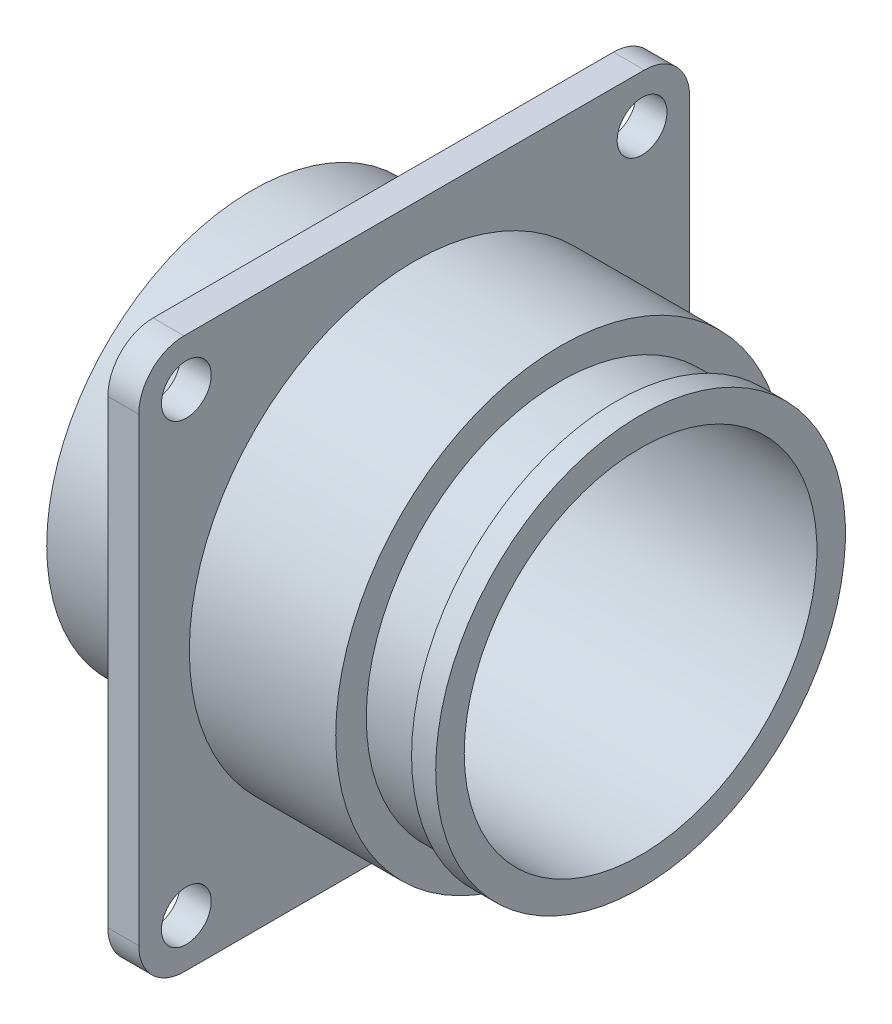
SolidWorks part; units mm, degrees
ref_plane "Alzado" through (0, 0, 0) normal (0, 0, 1) x (1, 0, 0)
ref_plane "Planta" through (0, 0, 0) normal (0, 1, 0) x (1, 0, 0)
ref_plane "Vista lateral" through (0, 0, 0) normal (1, 0, 0) x (0, 0, -1)
sketch "Croquis1" plane through (0, 0, 0) normal (1, 0, 0) x (0, 0, -1)
  line L1 (-15.25, -18.25) -> (15.25, -18.25)
  line L2 (-18.25, -15.25) -> (-18.25, 15.25)
  line L3 (-15.25, 18.25) -> (15.25, 18.25)
  line L4 (18.25, -15.25) -> (18.25, 15.25)
  line L5 (-18.25, -18.25) -> (18.25, 18.25) construction
  line L6 (-18.25, 18.25) -> (18.25, -18.25) construction
  line L7 (15.1, -15.1) -> (-15.1, -15.1) construction
  line L8 (15.1, -15.1) -> (15.1, 15.1) construction
  line L9 (15.1, 15.1) -> (-15.1, 15.1) construction
  line L10 (-15.1, -15.1) -> (-15.1, 15.1) construction
  line L11 (15.1, -15.1) -> (-15.1, 15.1) construction
  line L12 (15.1, 15.1) -> (-15.1, -15.1) construction
  circle A0 centre (-15.1, 15.1) radius 1.65
  circle A1 centre (-15.1, -15.1) radius 1.65
  circle A2 centre (15.1, -15.1) radius 1.65
  circle A3 centre (15.1, 15.1) radius 1.65
  arc A4 (15.25, 18.25) -> (18.25, 15.25) centre (15.25, 15.25) cw
  arc A5 (-18.25, 15.25) -> (-15.25, 18.25) centre (-15.25, 15.25) cw
  arc A6 (-15.25, -18.25) -> (-18.25, -15.25) centre (-15.25, -15.25) cw
  arc A7 (15.25, -18.25) -> (18.25, -15.25) centre (15.25, -15.25) ccw
  circle A8 centre (0, 0) radius 14.9
  point P0 (0, 0)
  point P6 (0, 0)
  dimension "D3" = 3.3
  dimension "D4" = 3
  dimension "D5" = 3
  dimension "D6" = 29.8
  dimension "D1" = 36.5
  dimension "D2" = 30.2
extrude "Saliente-Extruir1" add sketch "Croquis1" along normal blind 2.05
sketch "Croquis2" plane through (0, 0, 0) normal (0, 0, 1) x (1, 0, 0)
  line L0 (0, 14.9) -> (11.75, 14.9)
  line L1 (11.75, 12.875) -> (15.45, 12.875)
  line L2 (0, 0) -> (11.928, 0) construction
  line L3 (0, 15.25) -> (0, -15.25) construction
  line L4 (17.05, 11.685) -> (-3.25, 11.685)
  line L5 (15.45, 13.575) -> (17.05, 13.575)
  line L6 (17.05, 13.575) -> (17.05, 11.685)
  line L7 (15.45, 13.575) -> (15.45, 12.875)
  line L8 (2.05, 15.25) -> (2.05, -15.25) construction
  line L9 (11.75, 14.9) -> (11.75, 12.875)
  line L10 (0, 14.9) -> (0, 13.6)
  line L11 (0, 13.6) -> (-8.7, 13.6)
  line L12 (-8.7, 9) -> (-3.25, 9)
  line L13 (-8.7, 13.6) -> (-8.7, 9)
  line L14 (-3.25, 11.685) -> (-3.25, 9)
  dimension "D1" = 25.75
  dimension "D2" = 23.37
  dimension "D3" = 27.15
  dimension "D4" = 15
  dimension "D5" = 1.6
  dimension "D6" = 3.7
  dimension "D7" = 20.3
  dimension "D8" = 13.6
  dimension "D9" = 25.75
  dimension "D10" = 18
revolve "Revolución1" add sketch "Croquis2" angle 360 about L2
